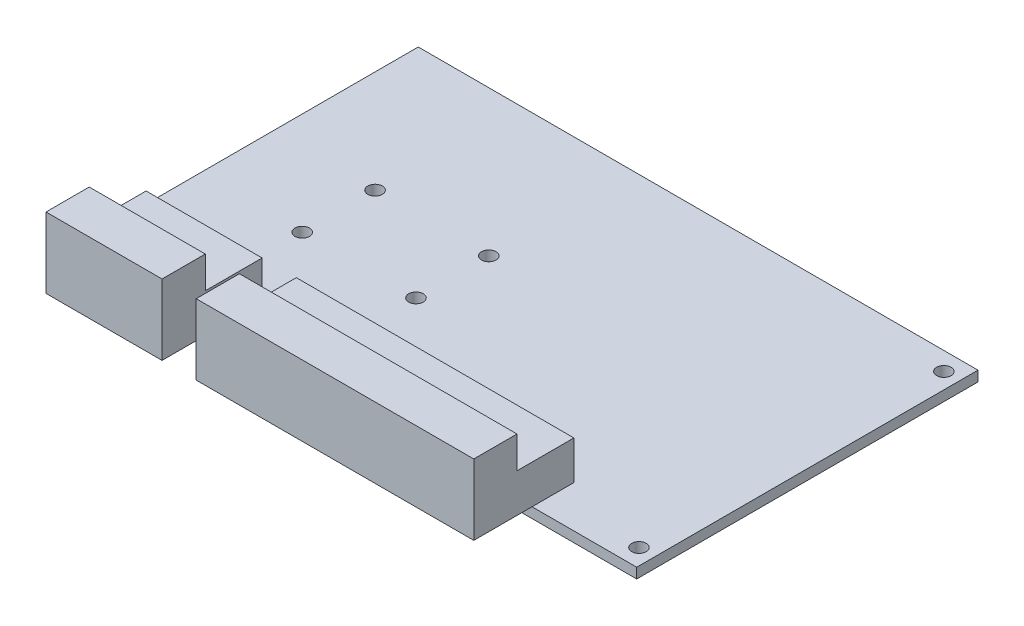
SolidWorks part; units mm, degrees
ref_plane "Front Plane" through (0, 0, 0) normal (0, 0, 1) x (1, 0, 0)
ref_plane "Top Plane" through (0, 0, 0) normal (0, 1, 0) x (1, 0, 0)
ref_plane "Right Plane" through (0, 0, 0) normal (1, 0, 0) x (0, 0, -1)
sketch "Sketch1" plane through (0, 0, 0) normal (0, 1, 0) x (1, 0, 0)
  line L0 (3.5, 4) -> (119.5, 4) construction
  line L1 (0, 0) -> (123, 0)
  line L2 (0, 0) -> (0, 75)
  line L3 (0, 75) -> (123, 75)
  line L4 (123, 0) -> (123, 75)
  line L5 (22.5, 43) -> (47.5, 43) construction
  line L6 (22.5, 43) -> (22.5, 27) construction
  line L7 (22.5, 27) -> (47.5, 27) construction
  line L8 (47.5, 43) -> (47.5, 27) construction
  line L9 (119.5, 4) -> (119.5, 71) construction
  circle A0 centre (119.5, 71) radius 1.6
  circle A1 centre (119.5, 4) radius 1.6
  circle A2 centre (3.5, 4) radius 1.6
  circle A3 centre (22.5, 43) radius 1.6
  circle A4 centre (47.5, 43) radius 1.6
  circle A5 centre (22.5, 27) radius 1.6
  circle A6 centre (47.5, 27) radius 1.6
  dimension "D3" = 3.2
  dimension "D1" = 75
  dimension "D2" = 123
  dimension "D4" = 3.5
  dimension "D5" = 4
  dimension "D6" = 3.5
  dimension "D7" = 25
  dimension "D8" = 16
  dimension "D9" = 19
  dimension "D10" = 23
  dimension "D11" = 4
extrude "Boss-Extrude1" add sketch "Sketch1" along normal blind 2.25
sketch "Sketch2" plane through (0, 2.25, 0) normal (0, 1, 0) x (1, 0, 0)
  line L0 (31.5, 9.2) -> (39, 9.2) construction
  line L1 (6, 9.2) -> (31.5, 9.2)
  line L2 (6, 9.2) -> (6, -12.8)
  line L3 (6, -12.8) -> (31.5, -12.8)
  line L4 (31.5, 9.2) -> (31.5, -12.8)
  line L5 (39, 9.2) -> (100, 9.2)
  line L6 (39, 9.2) -> (39, -12.8)
  line L7 (39, -12.8) -> (100, -12.8)
  line L8 (100, 9.2) -> (100, -12.8)
  line L9 (0, 0) -> (123, 0) construction
  line L10 (0, 75) -> (0, 0) construction
  line L11 (123, 0) -> (123, 75) construction
  line L12 (31.5, -12.8) -> (39, -12.8) construction
  dimension "D1" = 9.2
  dimension "D2" = 6
  dimension "D3" = 23
  dimension "D4" = 22
  dimension "D5" = 25.5
  dimension "D6" = 61
extrude "Boss-Extrude2" add sketch "Sketch2" along normal blind 8.5
sketch "Sketch3" plane through (0, 10.75, 0) normal (0, 1, 0) x (1, 0, 0)
  line L0 (31.5, -12.8) -> (31.5, 9.2) construction
  line L1 (6, -12.8) -> (31.5, -12.8)
  line L2 (6, -12.8) -> (6, -3.3)
  line L3 (6, -3.3) -> (31.5, -3.3)
  line L4 (31.5, -12.8) -> (31.5, -3.3)
  line L5 (100, -12.8) -> (100, 9.2) construction
  line L6 (39, -12.8) -> (100, -12.8)
  line L7 (39, -12.8) -> (39, -3.3)
  line L8 (39, -3.3) -> (100, -3.3)
  line L9 (100, -12.8) -> (100, -3.3)
  line L10 (31.5, -3.3) -> (39, -3.3) construction
  dimension "D1" = 9.5
extrude "Boss-Extrude3" add sketch "Sketch3" along normal blind 7
